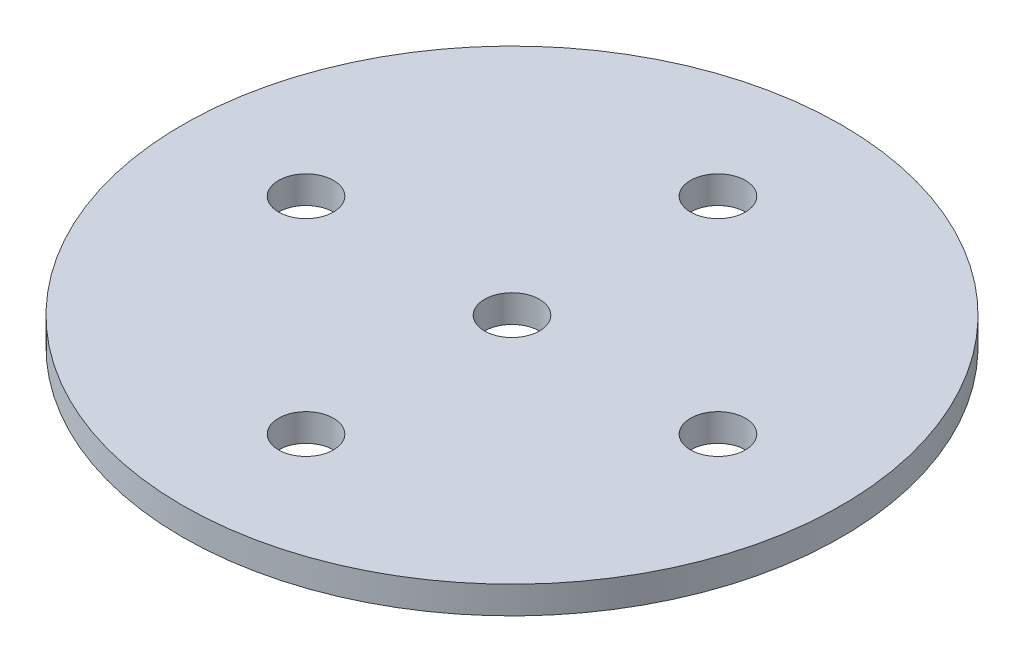
SolidWorks part; units mm, degrees
ref_plane "Front Plane" through (0, 0, 0) normal (0, 0, 1) x (1, 0, 0)
ref_plane "Top Plane" through (0, 0, 0) normal (0, 1, 0) x (1, 0, 0)
ref_plane "Right Plane" through (0, 0, 0) normal (1, 0, 0) x (0, 0, -1)
sketch "Sketch1" plane through (0, 0, 0) normal (0, 1, 0) x (1, 0, 0)
  line L0 (120, 0) -> (-120, 0) construction
  line L1 (0, 120) -> (0, -120) construction
  circle A0 centre (0, 0) radius 10
  circle A1 centre (75, 0) radius 10
  circle A2 centre (0, -75) radius 10
  circle A3 centre (-75, 0) radius 10
  circle A4 centre (0, 75) radius 10
  circle A5 centre (0, 0) radius 120
  dimension "D1" = 20
  dimension "D6" = 240
  dimension "D2" = 75
  dimension "D3" = 75
  dimension "D4" = 75
  dimension "D5" = 75
extrude "Boss-Extrude1" add sketch "Sketch1" along normal blind 10
